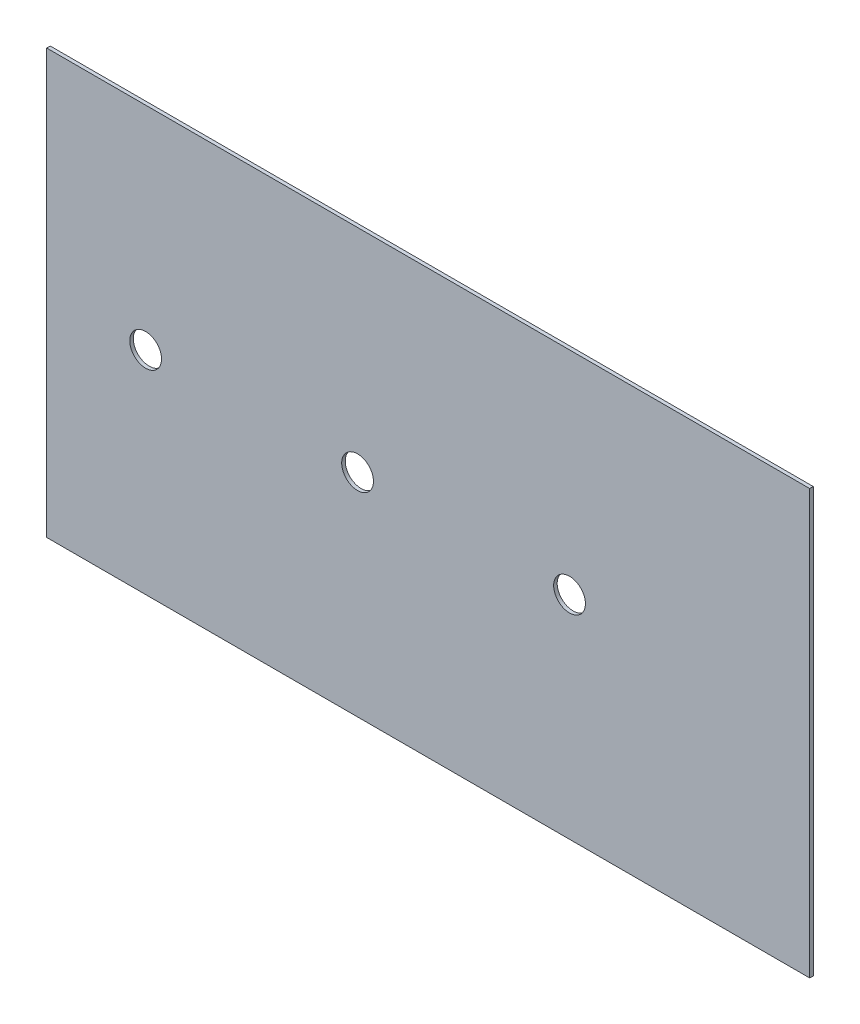
SolidWorks part; units mm, degrees
ref_plane "Front Plane" through (0, 0, 0) normal (0, 0, 1) x (1, 0, 0)
ref_plane "Top Plane" through (0, 0, 0) normal (0, 1, 0) x (1, 0, 0)
ref_plane "Right Plane" through (0, 0, 0) normal (1, 0, 0) x (0, 0, -1)
sketch "Sketch1" plane through (0, 0, 0) normal (0, 0, 1) x (1, 0, 0)
  line L1 (0, 0) -> (685.8, 0)
  line L2 (0, 0) -> (0, 381)
  line L3 (0, 381) -> (685.8, 381)
  line L4 (685.8, 0) -> (685.8, 381)
  dimension "D1" = 381
  dimension "D2" = 685.8
extrude "Boss-Extrude1" add sketch "Sketch1" along normal blind 3.175
sketch "Sketch2" plane through (0, 0, 3.175) normal (0, 0, 1) x (1, 0, 0)
  line L0 (685.8, 0) -> (469.9, 0)
  line L1 (0, 0) -> (685.8, 0) construction
  line L2 (469.9, 0) -> (469.9, 190.5) construction
  line L3 (469.9, 190.5) -> (88.9, 190.5) construction
  circle A0 centre (469.9, 190.5) radius 14.2875
  circle A1 centre (88.9, 190.5) radius 14.2875
  circle A2 centre (279.4, 190.5) radius 14.2875
  dimension "D3" = 28.575
  dimension "D1" = 215.9
  dimension "D2" = 190.5
  dimension "D4" = 381
extrude "Cut-Extrude1" cut sketch "Sketch2" against normal through all contours A1 | A2 | A0
